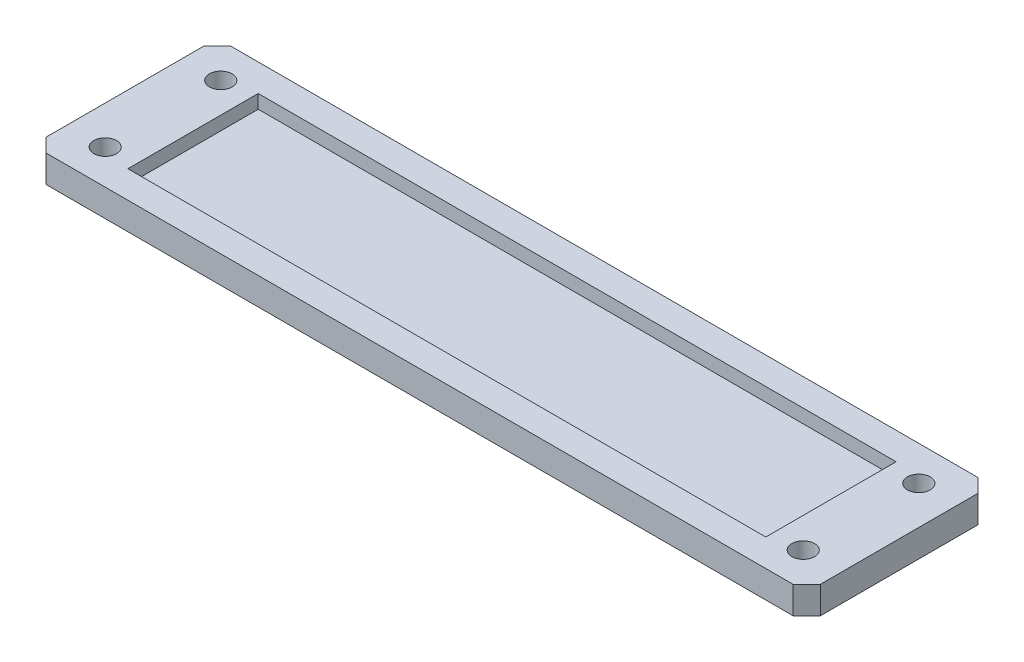
SolidWorks part; units mm, degrees
ref_plane "Front Plane" through (0, 0, 0) normal (0, 0, 1) x (1, 0, 0)
ref_plane "Top Plane" through (0, 0, 0) normal (0, 1, 0) x (1, 0, 0)
ref_plane "Right Plane" through (0, 0, 0) normal (1, 0, 0) x (0, 0, -1)
sketch "Sketch1" plane through (0, 0, 0) normal (0, 1, 0) x (1, 0, 0)
  line L0 (-85.09, 17.32) -> (-82.09, 20.32)
  line L1 (-82.09, -20.32) -> (82.09, -20.32)
  line L2 (-85.09, -17.32) -> (-85.09, 17.32)
  line L3 (-82.09, 20.32) -> (82.09, 20.32)
  line L4 (85.09, -17.32) -> (85.09, 17.32)
  line L5 (-85.09, -20.32) -> (85.09, 20.32) construction
  line L6 (-85.09, 20.32) -> (85.09, -20.32) construction
  line L7 (-85.09, -17.32) -> (-82.09, -20.32)
  line L8 (82.09, 20.32) -> (85.09, 17.32)
  line L9 (82.09, -20.32) -> (85.09, -17.32)
  circle A0 centre (-76.7, 12.7) radius 2.5
  circle A1 centre (-76.7, -12.7) radius 2.5
  circle A2 centre (76.7, 12.7) radius 2.5
  circle A3 centre (76.7, -12.7) radius 2.5
  point P0 (0, 0)
  dimension "D3" = 5
  dimension "D4" = 5
  dimension "D5" = 5
  dimension "D6" = 5
  dimension "D7" = 25.4
  dimension "D8" = 25.4
  dimension "D9" = 153.4
  dimension "D10" = 7.62
  dimension "D11" = 8.39
  dimension "D12" = 0
  dimension "D1" = 170.18
  dimension "D2" = 40.64
extrude "Boss-Extrude2" add sketch "Sketch1" along normal blind 6
sketch "Sketch2" plane through (0, 6, 0) normal (0, 1, 0) x (1, 0, 0)
  line L0 (82.09, 20.32) -> (-82.09, 20.32) construction
  line L1 (-70.09, 14.32) -> (70.09, 14.32)
  line L2 (-70.09, 14.32) -> (-70.09, -14.32)
  line L3 (-70.09, -14.32) -> (70.09, -14.32)
  line L4 (70.09, 14.32) -> (70.09, -14.32)
  line L5 (-70.09, 14.32) -> (70.09, -14.32) construction
  line L6 (-70.09, -14.32) -> (70.09, 14.32) construction
  line L7 (-85.09, 17.32) -> (-85.09, -17.32) construction
  point P0 (0, 0)
  dimension "D1" = 6
  dimension "D2" = 15
extrude "Cut-Extrude1" cut sketch "Sketch2" against normal blind 3
